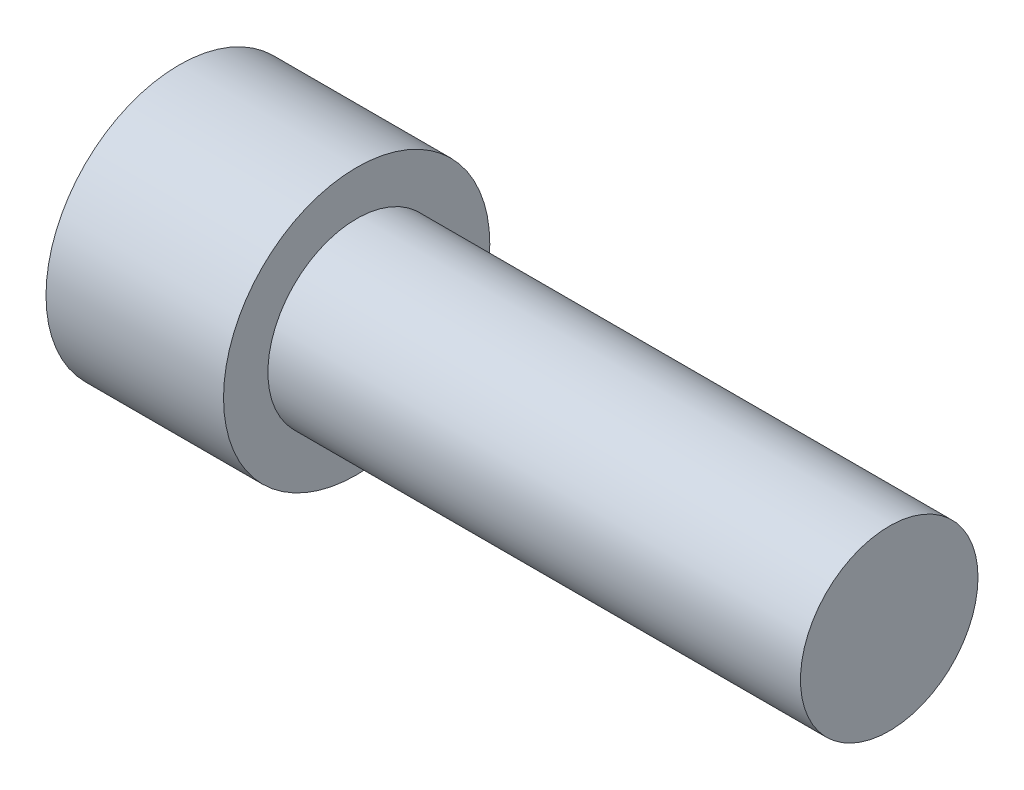
SolidWorks part; units mm, degrees
material "1023 Carbon Steel Sheet (SS)"
ref_plane "Front Plane" through (0, 0, 0) normal (0, 0, 1) x (1, 0, 0)
ref_plane "Top Plane" through (0, 0, 0) normal (0, 1, 0) x (1, 0, 0)
ref_plane "Right Plane" through (0, 0, 0) normal (1, 0, 0) x (0, 0, -1)
sketch "Sketch1" plane through (0, 0, 0) normal (1, 0, 0) x (0, 0, -1)
  circle A0 centre (0, 0) radius 3.175
  dimension "Thread_Diameter" = 6.35
extrude "Threaded_Screw" add sketch "Sketch1" along normal blind 19.05
sketch "Sketch2" plane through (0, 0, 0) normal (-1, 0, 0) x (0, 0, 1)
  circle A0 centre (0, 0) radius 4.7625
  dimension "Head Diameter" = 9.525
extrude "Round_Head" add sketch "Sketch2" along normal blind 6.35
sketch "Sketch3" plane through (-6.35, 0, 0) normal (-1, 0, 0) x (0, 0, 1)
  line L0 (0, -5.2388) -> (0, 5.2388) construction
  line L1 (2.3812, -1.3748) -> (2.3812, 1.3748)
  line L2 (2.3812, 1.3748) -> (0, 2.7496)
  line L3 (0, 2.7496) -> (-2.3812, 1.3748)
  line L4 (-2.3812, 1.3748) -> (-2.3813, -1.3748)
  line L5 (-2.3813, -1.3748) -> (0, -2.7496)
  line L6 (0, -2.7496) -> (2.3812, -1.3748)
  circle A0 centre (0, 0) radius 2.3812 construction
  dimension "D1" = 4.7625
extrude "Hex_Socket_Size" cut sketch "Sketch3" against normal blind 4
